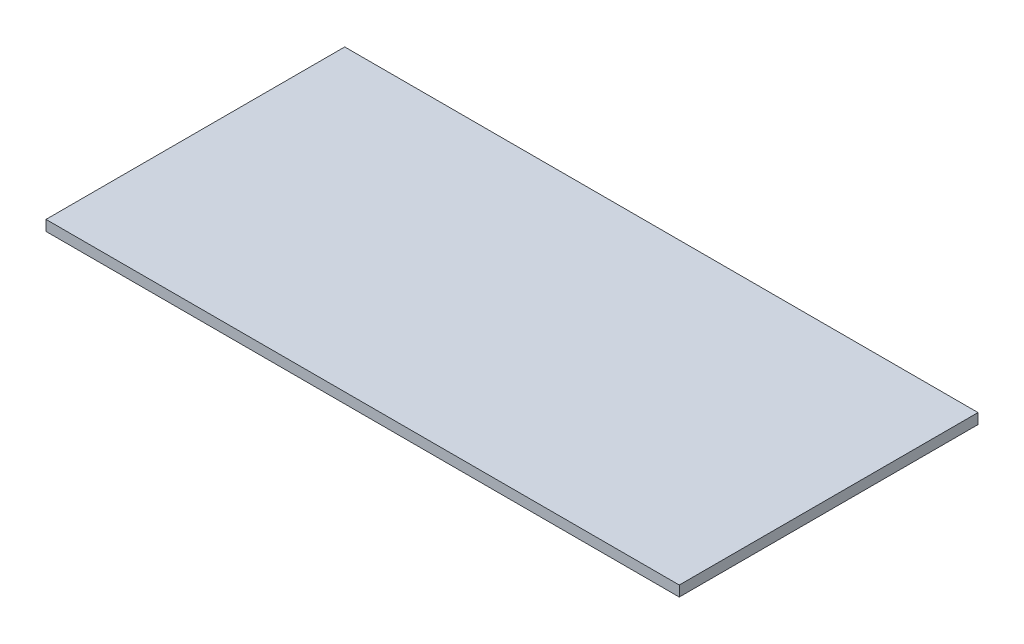
SolidWorks part; units mm, degrees
material "Plain Carbon Steel"
ref_plane "Front Plane" through (0, 0, 0) normal (0, 0, 1) x (1, 0, 0)
ref_plane "Top Plane" through (0, 0, 0) normal (0, 1, 0) x (1, 0, 0)
ref_plane "Right Plane" through (0, 0, 0) normal (1, 0, 0) x (0, 0, -1)
sketch "Sketch1" plane through (0, 0, 0) normal (0, 1, 0) x (1, 0, 0)
  line L0 (-34.0726, 25.0693) -> (177.9274, 25.0693)
  line L1 (177.9274, 25.0693) -> (177.9274, -74.9307)
  line L2 (177.9274, -74.9307) -> (-34.0726, -74.9307)
  line L3 (-34.0726, -74.9307) -> (-34.0726, 25.0693)
  dimension "D1" = 212
extrude "Boss-Extrude1" add sketch "Sketch1" along normal blind 3.5
